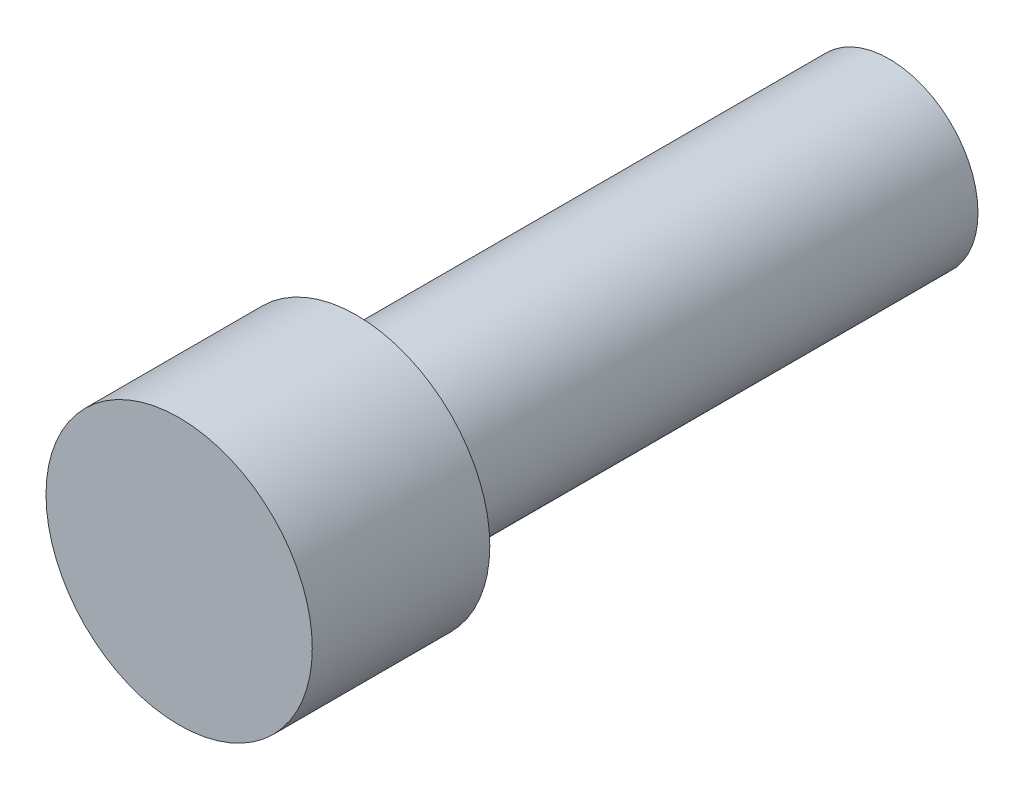
SolidWorks part; units mm, degrees
ref_plane "前视基准面" through (0, 0, 0) normal (0, 0, 1) x (1, 0, 0)
ref_plane "上视基准面" through (0, 0, 0) normal (0, 1, 0) x (1, 0, 0)
ref_plane "右视基准面" through (0, 0, 0) normal (1, 0, 0) x (0, 0, -1)
other "Configuration Table"
sketch "Sketch1" plane through (0, 0, 0) normal (0, 0, 1) x (1, 0, 0)
  circle A0 centre (0, 0) radius 5
  dimension "D1" = 10
extrude "Boss-Extrude1" add sketch "Sketch1" along normal blind 30
sketch "Sketch2" plane through (0, 0, 30) normal (0, 0, 1) x (1, 0, 0)
  circle A0 centre (0, 0) radius 7.5
  dimension "D1" = 15
extrude "Boss-Extrude2" add sketch "Sketch2" along normal blind 10
